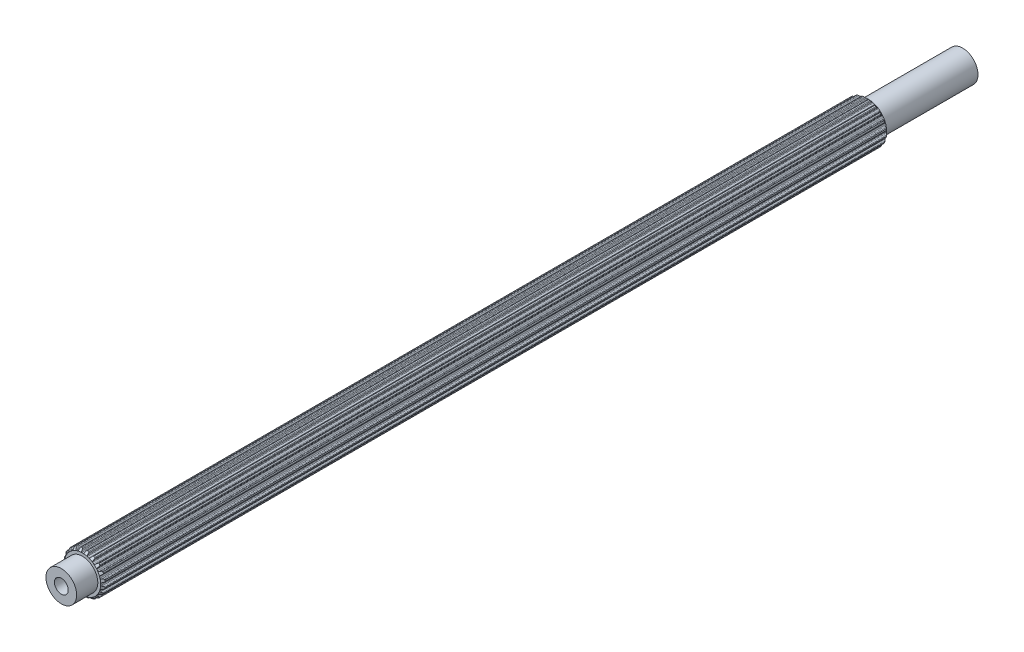
SolidWorks part; units mm, degrees
ref_plane "Front Plane" through (0, 0, 0) normal (0, 0, 1) x (1, 0, 0)
ref_plane "Top Plane" through (0, 0, 0) normal (0, 1, 0) x (1, 0, 0)
ref_plane "Right Plane" through (0, 0, 0) normal (1, 0, 0) x (0, 0, -1)
sketch "Sketch1" plane through (0, 0, 0) normal (0, 0, 1) x (1, 0, 0)
  line L0 (-0.1069, 2.9699) -> (0.1069, 2.9699)
  line L1 (0.3159, 3.2375) -> (0.2537, 3.0575)
  line L2 (-0.2964, 3.2367) -> (-0.2318, 3.0575)
  line L3 (-0.2964, 3.2367) -> (0.3159, 3.2375) construction
  line L4 (0, 3.3252) -> (0, 0) construction
  line L5 (-0.2318, 3.0575) -> (0.2537, 3.0575) construction
  line L6 (-0.4281, 3.3241) -> (0.4281, 3.3263) construction
  line L7 (0.7183, 3.1698) -> (0.7244, 2.9795)
  line L8 (0.816, 2.8576) -> (1.0195, 2.7915)
  line L9 (1.3009, 2.9815) -> (1.1862, 2.8295)
  line L10 (1.6627, 2.7927) -> (1.6097, 2.6099)
  line L11 (1.6591, 2.4655) -> (1.8322, 2.3398)
  line L12 (2.1585, 2.4335) -> (2.0025, 2.3245)
  line L13 (2.4443, 2.1423) -> (2.3374, 1.9847)
  line L14 (2.3398, 1.8322) -> (2.4655, 1.6591)
  line L15 (2.8049, 1.6474) -> (2.6228, 1.5919)
  line L16 (2.9866, 1.2821) -> (2.8363, 1.1653)
  line L17 (2.7915, 1.0195) -> (2.8576, 0.816)
  line L18 (3.1767, 0.7) -> (2.9863, 0.7035)
  line L19 (3.2367, 0.2964) -> (3.0575, 0.2318)
  line L20 (2.9699, 0.1069) -> (2.9699, -0.1069)
  line L21 (3.2375, -0.3159) -> (3.0575, -0.2537)
  line L22 (3.1698, -0.7183) -> (2.9795, -0.7244)
  line L23 (2.8576, -0.816) -> (2.7915, -1.0195)
  line L24 (2.9815, -1.3009) -> (2.8295, -1.1862)
  line L25 (2.7927, -1.6627) -> (2.6099, -1.6097)
  line L26 (2.4655, -1.6591) -> (2.3398, -1.8322)
  line L27 (2.4335, -2.1585) -> (2.3245, -2.0025)
  line L28 (2.1423, -2.4443) -> (1.9847, -2.3374)
  line L29 (1.8322, -2.3398) -> (1.6591, -2.4655)
  line L30 (1.6474, -2.8049) -> (1.5919, -2.6228)
  line L31 (1.2821, -2.9866) -> (1.1653, -2.8363)
  line L32 (1.0195, -2.7915) -> (0.816, -2.8576)
  line L33 (0.7, -3.1767) -> (0.7035, -2.9863)
  line L34 (0.2964, -3.2367) -> (0.2318, -3.0575)
  line L35 (0.1069, -2.9699) -> (-0.1069, -2.9699)
  line L36 (-0.3159, -3.2375) -> (-0.2537, -3.0575)
  line L37 (-0.7183, -3.1698) -> (-0.7244, -2.9795)
  line L38 (-0.816, -2.8576) -> (-1.0195, -2.7915)
  line L39 (-1.3009, -2.9815) -> (-1.1862, -2.8295)
  line L40 (-1.6627, -2.7927) -> (-1.6097, -2.6099)
  line L41 (-1.6591, -2.4655) -> (-1.8322, -2.3398)
  line L42 (-2.1585, -2.4335) -> (-2.0025, -2.3245)
  line L43 (-2.4443, -2.1423) -> (-2.3374, -1.9847)
  line L44 (-2.3398, -1.8322) -> (-2.4655, -1.6591)
  line L45 (-2.8049, -1.6474) -> (-2.6228, -1.5919)
  line L46 (-2.9866, -1.2821) -> (-2.8363, -1.1653)
  line L47 (-2.7915, -1.0195) -> (-2.8576, -0.816)
  line L48 (-3.1767, -0.7) -> (-2.9863, -0.7035)
  line L49 (-3.2367, -0.2964) -> (-3.0575, -0.2318)
  line L50 (-2.9699, -0.1069) -> (-2.9699, 0.1069)
  line L51 (-3.2375, 0.3159) -> (-3.0575, 0.2537)
  line L52 (-3.1698, 0.7183) -> (-2.9795, 0.7244)
  line L53 (-2.8576, 0.816) -> (-2.7915, 1.0195)
  line L54 (-2.9815, 1.3009) -> (-2.8295, 1.1862)
  line L55 (-2.7927, 1.6627) -> (-2.6099, 1.6097)
  line L56 (-2.4655, 1.6591) -> (-2.3398, 1.8322)
  line L57 (-2.4335, 2.1585) -> (-2.3245, 2.0025)
  line L58 (-2.1423, 2.4443) -> (-1.9847, 2.3374)
  line L59 (-1.8322, 2.3398) -> (-1.6591, 2.4655)
  line L60 (-1.6474, 2.8049) -> (-1.5919, 2.6228)
  line L61 (-1.2821, 2.9866) -> (-1.1653, 2.8363)
  line L62 (-1.0195, 2.7915) -> (-0.816, 2.8576)
  line L63 (-0.7, 3.1767) -> (-0.7035, 2.9863)
  line L64 (0.4281, 3.3263) -> (0.62, 3.2938)
  line L65 (1.4351, 3.0312) -> (1.6075, 2.9409)
  line L66 (2.3015, 2.4394) -> (2.4376, 2.3003)
  line L67 (2.9427, 1.6088) -> (3.0291, 1.4344)
  line L68 (3.2958, 0.6207) -> (3.3241, 0.4281)
  line L69 (3.3263, -0.4281) -> (3.2938, -0.62)
  line L70 (3.0312, -1.4351) -> (2.9409, -1.6075)
  line L71 (2.4394, -2.3015) -> (2.3003, -2.4376)
  line L72 (1.6088, -2.9427) -> (1.4344, -3.0291)
  line L73 (0.6207, -3.2958) -> (0.4281, -3.3241)
  line L74 (-0.4281, -3.3263) -> (-0.62, -3.2938)
  line L75 (-1.4351, -3.0312) -> (-1.6075, -2.9409)
  line L76 (-2.3015, -2.4394) -> (-2.4376, -2.3003)
  line L77 (-2.9427, -1.6088) -> (-3.0291, -1.4344)
  line L78 (-3.2958, -0.6207) -> (-3.3241, -0.4281)
  line L79 (-3.3263, 0.4281) -> (-3.2938, 0.62)
  line L80 (-3.0312, 1.4351) -> (-2.9409, 1.6075)
  line L81 (-2.4394, 2.3015) -> (-2.3003, 2.4376)
  line L82 (-1.6088, 2.9427) -> (-1.4344, 3.0291)
  line L83 (-0.6207, 3.2958) -> (-0.4281, 3.3241)
  arc A0 (0.2537, 3.0575) -> (0.1069, 2.9699) centre (0.1283, 3.1009) cw
  arc A1 (-0.2318, 3.0575) -> (-0.1069, 2.9699) centre (-0.1069, 3.1026) ccw
  arc A2 (0.62, 3.2938) -> (0.7183, 3.1698) centre (0.5856, 3.1656) cw
  arc A3 (0.7244, 2.9795) -> (0.816, 2.8576) centre (0.857, 2.9838) ccw
  arc A4 (-0.4281, 3.3241) -> (-0.2964, 3.2367) centre (-0.4213, 3.1916) cw
  arc A5 (0.4281, 3.3263) -> (0.3159, 3.2375) centre (0.4413, 3.1942) ccw
  arc A6 (1.1862, 2.8295) -> (1.0195, 2.7915) centre (1.0802, 2.9095) cw
  arc A7 (1.4351, 3.0312) -> (1.3009, 2.9815) centre (1.4068, 2.9015) ccw
  arc A8 (1.6075, 2.9409) -> (1.6627, 2.7927) centre (1.5352, 2.8297) cw
  arc A9 (1.6097, 2.6099) -> (1.6591, 2.4655) centre (1.7371, 2.5729) ccw
  arc A10 (2.0025, 2.3245) -> (1.8322, 2.3398) centre (1.9264, 2.4332) cw
  arc A11 (2.3015, 2.4394) -> (2.1585, 2.4335) centre (2.2346, 2.3248) ccw
  arc A12 (2.4376, 2.3003) -> (2.4443, 2.1423) centre (2.3345, 2.2168) cw
  arc A13 (2.3374, 1.9847) -> (2.3398, 1.8322) centre (2.4472, 1.9102) ccw
  arc A14 (2.6228, 1.5919) -> (2.4655, 1.6591) centre (2.5841, 1.7189) cw
  arc A15 (2.9427, 1.6088) -> (2.8049, 1.6474) centre (2.8436, 1.5205) ccw
  arc A16 (3.0291, 1.4344) -> (2.9866, 1.2821) centre (2.9052, 1.3869) cw
  arc A17 (2.8363, 1.1653) -> (2.7915, 1.0195) centre (2.9177, 1.0605) ccw
  arc A18 (2.9863, 0.7035) -> (2.8576, 0.816) centre (2.9887, 0.8362) cw
  arc A19 (3.2958, 0.6207) -> (3.1767, 0.7) centre (3.1743, 0.5673) ccw
  arc A20 (3.3241, 0.4281) -> (3.2367, 0.2964) centre (3.1916, 0.4213) cw
  arc A21 (3.0575, 0.2318) -> (2.9699, 0.1069) centre (3.1026, 0.1069) ccw
  arc A22 (3.0575, -0.2537) -> (2.9699, -0.1069) centre (3.1009, -0.1283) cw
  arc A23 (3.3263, -0.4281) -> (3.2375, -0.3159) centre (3.1942, -0.4413) ccw
  arc A24 (3.2938, -0.62) -> (3.1698, -0.7183) centre (3.1656, -0.5856) cw
  arc A25 (2.9795, -0.7244) -> (2.8576, -0.816) centre (2.9838, -0.857) ccw
  arc A26 (2.8295, -1.1862) -> (2.7915, -1.0195) centre (2.9095, -1.0802) cw
  arc A27 (3.0312, -1.4351) -> (2.9815, -1.3009) centre (2.9015, -1.4068) ccw
  arc A28 (2.9409, -1.6075) -> (2.7927, -1.6627) centre (2.8297, -1.5352) cw
  arc A29 (2.6099, -1.6097) -> (2.4655, -1.6591) centre (2.5729, -1.7371) ccw
  arc A30 (2.3245, -2.0025) -> (2.3398, -1.8322) centre (2.4332, -1.9264) cw
  arc A31 (2.4394, -2.3015) -> (2.4335, -2.1585) centre (2.3248, -2.2346) ccw
  arc A32 (2.3003, -2.4376) -> (2.1423, -2.4443) centre (2.2168, -2.3345) cw
  arc A33 (1.9847, -2.3374) -> (1.8322, -2.3398) centre (1.9102, -2.4472) ccw
  arc A34 (1.5919, -2.6228) -> (1.6591, -2.4655) centre (1.7189, -2.5841) cw
  arc A35 (1.6088, -2.9427) -> (1.6474, -2.8049) centre (1.5205, -2.8436) ccw
  arc A36 (1.4344, -3.0291) -> (1.2821, -2.9866) centre (1.3869, -2.9052) cw
  arc A37 (1.1653, -2.8363) -> (1.0195, -2.7915) centre (1.0605, -2.9177) ccw
  arc A38 (0.7035, -2.9863) -> (0.816, -2.8576) centre (0.8362, -2.9887) cw
  arc A39 (0.6207, -3.2958) -> (0.7, -3.1767) centre (0.5673, -3.1743) ccw
  arc A40 (0.4281, -3.3241) -> (0.2964, -3.2367) centre (0.4213, -3.1916) cw
  arc A41 (0.2318, -3.0575) -> (0.1069, -2.9699) centre (0.1069, -3.1026) ccw
  arc A42 (-0.2537, -3.0575) -> (-0.1069, -2.9699) centre (-0.1283, -3.1009) cw
  arc A43 (-0.4281, -3.3263) -> (-0.3159, -3.2375) centre (-0.4413, -3.1942) ccw
  arc A44 (-0.62, -3.2938) -> (-0.7183, -3.1698) centre (-0.5856, -3.1656) cw
  arc A45 (-0.7244, -2.9795) -> (-0.816, -2.8576) centre (-0.857, -2.9838) ccw
  arc A46 (-1.1862, -2.8295) -> (-1.0195, -2.7915) centre (-1.0802, -2.9095) cw
  arc A47 (-1.4351, -3.0312) -> (-1.3009, -2.9815) centre (-1.4068, -2.9015) ccw
  arc A48 (-1.6075, -2.9409) -> (-1.6627, -2.7927) centre (-1.5352, -2.8297) cw
  arc A49 (-1.6097, -2.6099) -> (-1.6591, -2.4655) centre (-1.7371, -2.5729) ccw
  arc A50 (-2.0025, -2.3245) -> (-1.8322, -2.3398) centre (-1.9264, -2.4332) cw
  arc A51 (-2.3015, -2.4394) -> (-2.1585, -2.4335) centre (-2.2346, -2.3248) ccw
  arc A52 (-2.4376, -2.3003) -> (-2.4443, -2.1423) centre (-2.3345, -2.2168) cw
  arc A53 (-2.3374, -1.9847) -> (-2.3398, -1.8322) centre (-2.4472, -1.9102) ccw
  arc A54 (-2.6228, -1.5919) -> (-2.4655, -1.6591) centre (-2.5841, -1.7189) cw
  arc A55 (-2.9427, -1.6088) -> (-2.8049, -1.6474) centre (-2.8436, -1.5205) ccw
  arc A56 (-3.0291, -1.4344) -> (-2.9866, -1.2821) centre (-2.9052, -1.3869) cw
  arc A57 (-2.8363, -1.1653) -> (-2.7915, -1.0195) centre (-2.9177, -1.0605) ccw
  arc A58 (-2.9863, -0.7035) -> (-2.8576, -0.816) centre (-2.9887, -0.8362) cw
  arc A59 (-3.2958, -0.6207) -> (-3.1767, -0.7) centre (-3.1743, -0.5673) ccw
  arc A60 (-3.3241, -0.4281) -> (-3.2367, -0.2964) centre (-3.1916, -0.4213) cw
  arc A61 (-3.0575, -0.2318) -> (-2.9699, -0.1069) centre (-3.1026, -0.1069) ccw
  arc A62 (-3.0575, 0.2537) -> (-2.9699, 0.1069) centre (-3.1009, 0.1283) cw
  arc A63 (-3.3263, 0.4281) -> (-3.2375, 0.3159) centre (-3.1942, 0.4413) ccw
  arc A64 (-3.2938, 0.62) -> (-3.1698, 0.7183) centre (-3.1656, 0.5856) cw
  arc A65 (-2.9795, 0.7244) -> (-2.8576, 0.816) centre (-2.9838, 0.857) ccw
  arc A66 (-2.8295, 1.1862) -> (-2.7915, 1.0195) centre (-2.9095, 1.0802) cw
  arc A67 (-3.0312, 1.4351) -> (-2.9815, 1.3009) centre (-2.9015, 1.4068) ccw
  arc A68 (-2.9409, 1.6075) -> (-2.7927, 1.6627) centre (-2.8297, 1.5352) cw
  arc A69 (-2.6099, 1.6097) -> (-2.4655, 1.6591) centre (-2.5729, 1.7371) ccw
  arc A70 (-2.3245, 2.0025) -> (-2.3398, 1.8322) centre (-2.4332, 1.9264) cw
  arc A71 (-2.4394, 2.3015) -> (-2.4335, 2.1585) centre (-2.3248, 2.2346) ccw
  arc A72 (-2.3003, 2.4376) -> (-2.1423, 2.4443) centre (-2.2168, 2.3345) cw
  arc A73 (-1.9847, 2.3374) -> (-1.8322, 2.3398) centre (-1.9102, 2.4472) ccw
  arc A74 (-1.5919, 2.6228) -> (-1.6591, 2.4655) centre (-1.7189, 2.5841) cw
  arc A75 (-1.6088, 2.9427) -> (-1.6474, 2.8049) centre (-1.5205, 2.8436) ccw
  arc A76 (-1.4344, 3.0291) -> (-1.2821, 2.9866) centre (-1.3869, 2.9052) cw
  arc A77 (-1.1653, 2.8363) -> (-1.0195, 2.7915) centre (-1.0605, 2.9177) ccw
  arc A78 (-0.7035, 2.9863) -> (-0.816, 2.8576) centre (-0.8362, 2.9887) cw
  arc A79 (-0.6207, 3.2958) -> (-0.7, 3.1767) centre (-0.5673, 3.1743) ccw
  point P14 (0, 2.9699)
  point P247 (0, 0)
  dimension "D4" = 0.1327
  dimension "D8" = 20
  dimension "D1" = 2.9699
  dimension "D2" = 0.2139
  dimension "D3" = 0.1904
  dimension "D5" = 0.0877
  dimension "D6" = 0.4855
  dimension "D7" = 0.8563
extrude "Boss-Extrude1" add sketch "Sketch1" along normal blind 70.0786 and the other way blind 58.1406
sketch "Sketch2" plane through (0, 0, 0) normal (0, 0, 1) x (1, 0, 0)
  circle A0 centre (0, 0) radius 2.5019
  dimension "D1" = 5.0038
extrude "Boss-Extrude2" add sketch "Sketch2" along normal mid plane 147.066
sketch "Sketch4" plane through (0, 0, 73.533) normal (0, 0, 1) x (1, 0, 0)
  circle A0 centre (0, 0) radius 2.5019 construction
  point P0 (0, 0)
sketch "Sketch5" plane through (0, 0, -73.533) normal (0, 0, -1) x (-1, 0, 0)
  circle A0 centre (0, 0) radius 2.5019 construction
  point P0 (0, 0)
sketch "Sketch3" plane through (0, 0, 0) normal (1, 0, 0) x (0, 0, -1)
  line L0 (-68.9474, 4.1011) -> (-70.0786, 2.9699)
  line L1 (-70.0786, 2.9699) -> (-70.0786, 4.1011)
  line L2 (-70.0786, 4.1011) -> (-68.9474, 4.1011)
  line L3 (-70.0786, 2.5019) -> (-70.0786, -2.5019) construction
  line L5 (-14.3608, 0) -> (13.2171, 0) construction
  line L7 (58.1406, 54.8545) -> (58.1406, 2.9699)
  line L8 (58.1406, 2.9699) -> (32.1983, 28.9122)
  line L9 (32.1983, 28.9122) -> (58.1406, 54.8545)
  line L10 (58.1406, -2.5019) -> (58.1406, 2.5019) construction
  point P6 (-4.866, 6.1438)
  dimension "D1" = 45
  dimension "D2" = 45
revolve "Cut-Revolve1" cut sketch "Sketch3" angle 360 about L5
sketch "Sketch6" plane through (0, 0, 0) normal (0, 0, 1) x (1, 0, 0)
  circle A0 centre (0, 0) radius 1.1303
  point P2 (6.1303, -6.5438)
  dimension "D1" = 2.2606
extrude "Cut-Extrude1" cut sketch "Sketch6" along normal up to surface and the other way up to surface up to face at (2.5019, 0, 73.533) other way up to face at (2.5019, 0, -73.533)
sketch "Sketch7" plane through (0, 0, 0) normal (0, 0, 1) x (1, 0, 0)
  circle A0 centre (0, 0) radius 1.1303
  circle A1 centre (0, 0) radius 1.1303 construction
  point P2 (4.2063, -11.8843)
extrude "Boss-Extrude3" add sketch "Sketch7" along normal offset from surface 9.525 and the other way offset from surface (64.008 mm away) 9.525 up to face at (1.1303, 0, 73.533) other way up to face at (1.1303, 0, -73.533)
